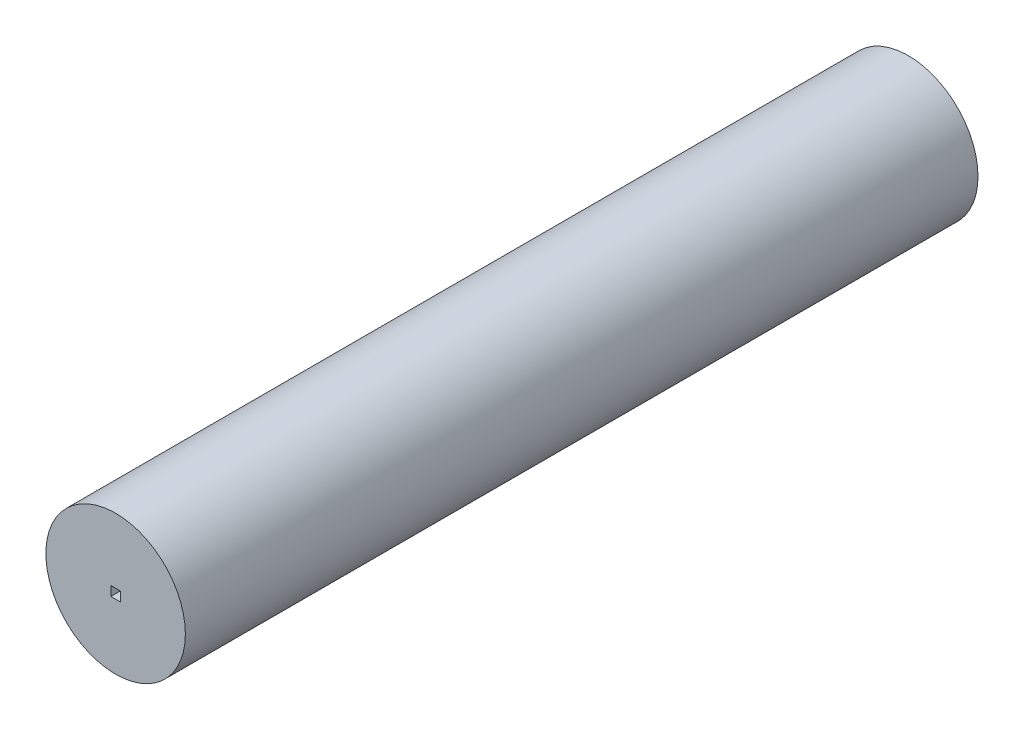
SolidWorks part; units mm, degrees
ref_plane "Plan de face" through (0, 0, 0) normal (0, 0, 1) x (1, 0, 0)
ref_plane "Plan de dessus" through (0, 0, 0) normal (0, 1, 0) x (1, 0, 0)
ref_plane "Plan de droite" through (0, 0, 0) normal (1, 0, 0) x (0, 0, -1)
sketch "Esquisse1" plane through (0, 0, 0) normal (0, 0, 1) x (1, 0, 0)
  circle A0 centre (0, 0) radius 22
extrude "Boss.-Extru.1" add sketch "Esquisse1" along normal blind 250
sketch "Esquisse2" plane through (0, 0, 250) normal (0, 0, 1) x (1, 0, 0)
  line L1 (1.5, 1.5) -> (-1.5, 1.5)
  line L2 (1.5, 1.5) -> (1.5, -1.5)
  line L3 (1.5, -1.5) -> (-1.5, -1.5)
  line L4 (-1.5, 1.5) -> (-1.5, -1.5)
  line L5 (1.5, 1.5) -> (-1.5, -1.5) construction
  line L6 (1.5, -1.5) -> (-1.5, 1.5) construction
  point P0 (0, 0)
  dimension "D1" = 3
  dimension "D2" = 3
extrude "Enlèv. mat.-Extru.1" cut sketch "Esquisse2" against normal blind 120
